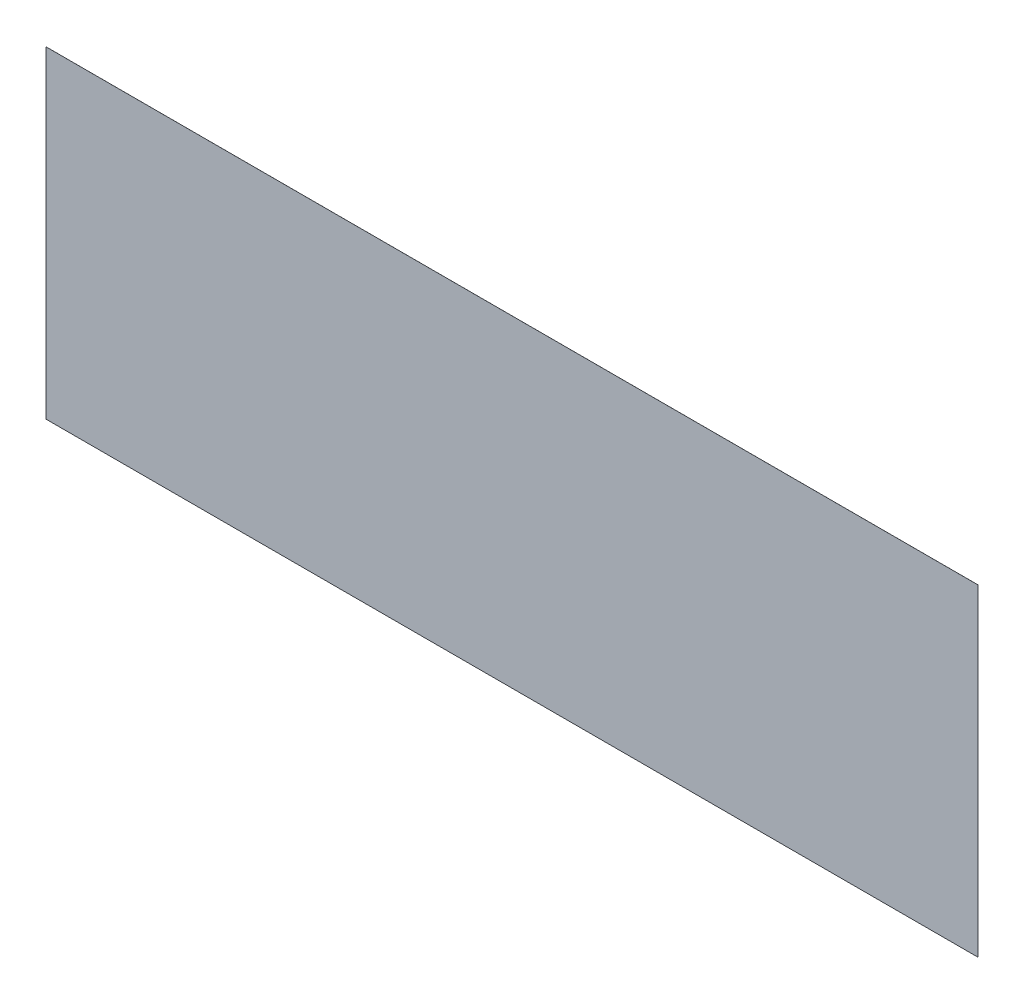
SolidWorks part; units mm, degrees
material "Polyester Resin"
ref_plane "Front Plane" through (0, 0, 0) normal (0, 0, 1) x (1, 0, 0)
ref_plane "Top Plane" through (0, 0, 0) normal (0, 1, 0) x (1, 0, 0)
ref_plane "Right Plane" through (0, 0, 0) normal (1, 0, 0) x (0, 0, -1)
sketch "Sketch2" plane through (0, 0, 0) normal (0, 0, 1) x (1, 0, 0)
  line L1 (0, 0) -> (2890, 0)
  line L2 (0, 0) -> (0, -1000)
  line L3 (0, -1000) -> (2890, -1000)
  line L4 (2890, 0) -> (2890, -1000)
  dimension "D1" = 2890
  dimension "D2" = 1000
extrude "Boss-Extrude1" add sketch "Sketch2" along normal blind 0.1
